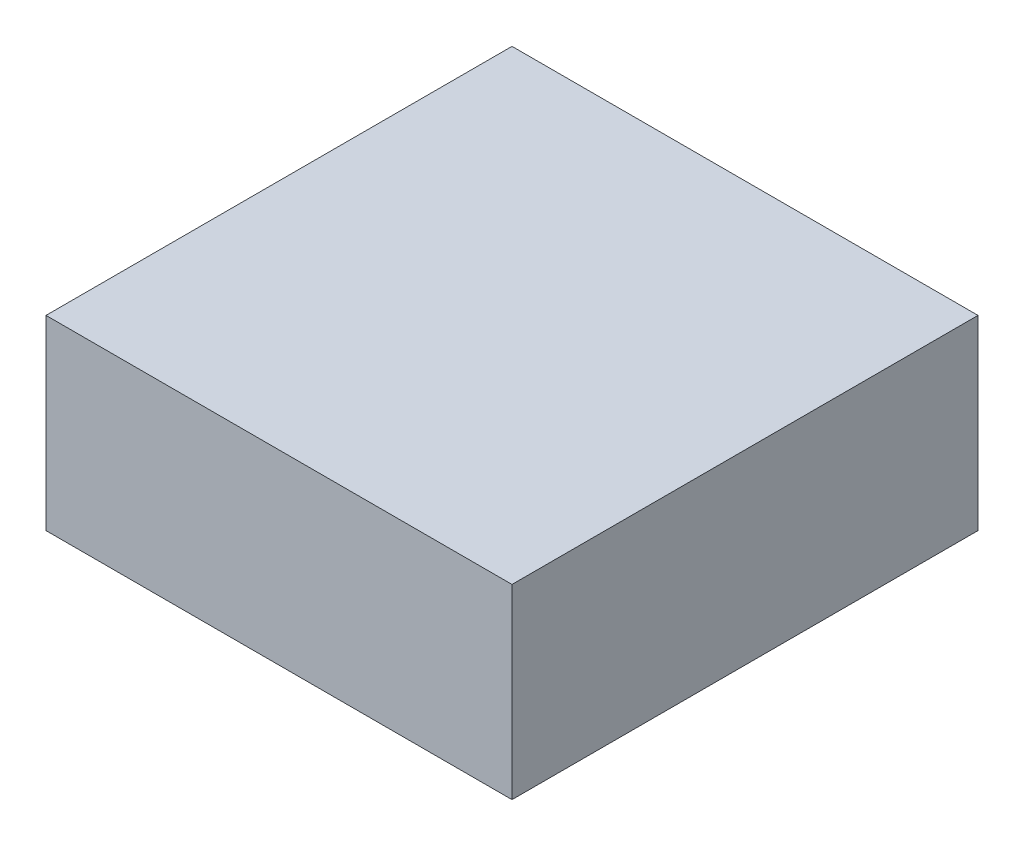
SolidWorks part; units mm, degrees
ref_plane "前视基准面" through (0, 0, 0) normal (0, 0, 1) x (1, 0, 0)
ref_plane "上视基准面" through (0, 0, 0) normal (0, 1, 0) x (1, 0, 0)
ref_plane "右视基准面" through (0, 0, 0) normal (1, 0, 0) x (0, 0, -1)
sketch "草图1" plane through (0, 0, 0) normal (0, 1, 0) x (1, 0, 0)
  line L1 (-62.5, 62.5) -> (62.5, 62.5)
  line L2 (-62.5, 62.5) -> (-62.5, -62.5)
  line L3 (-62.5, -62.5) -> (62.5, -62.5)
  line L4 (62.5, 62.5) -> (62.5, -62.5)
  line L5 (-62.5, 62.5) -> (62.5, -62.5) construction
  line L6 (-62.5, -62.5) -> (62.5, 62.5) construction
  point P0 (0, 0)
  dimension "D1" = 125
  dimension "D2" = 125
extrude "凸台-拉伸1" add sketch "草图1" along normal blind 50
